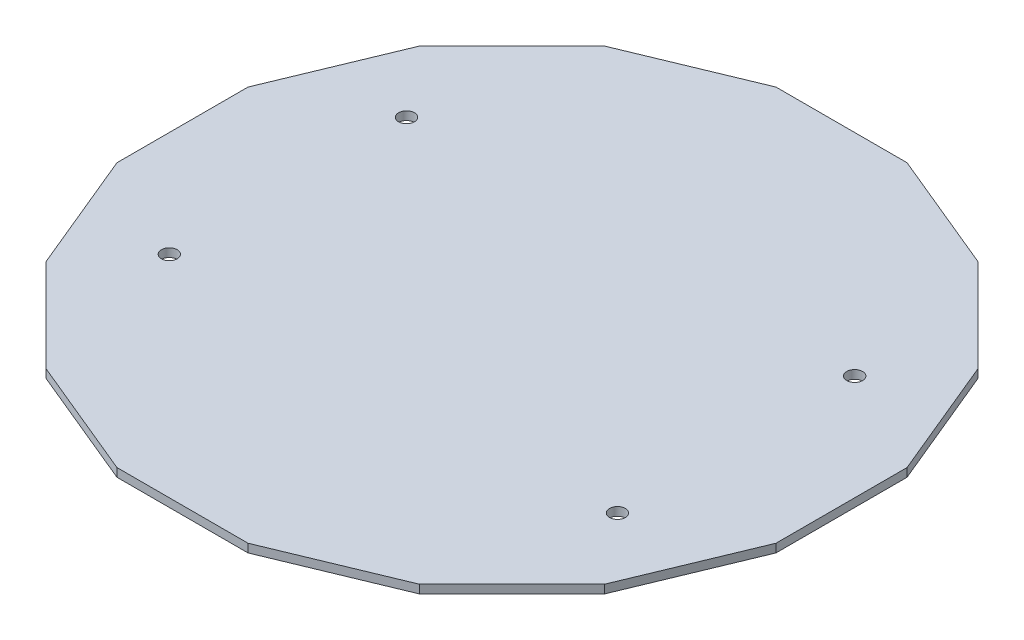
SolidWorks part; units mm, degrees
ref_plane "Front Plane" through (0, 0, 0) normal (0, 0, 1) x (1, 0, 0)
ref_plane "Top Plane" through (0, 0, 0) normal (0, 1, 0) x (1, 0, 0)
ref_plane "Right Plane" through (0, 0, 0) normal (1, 0, 0) x (0, 0, -1)
sketch "Sketch1" plane through (0, 0, 0) normal (0, 1, 0) x (1, 0, 0)
  line L1 (62.5, 12.432) -> (52.9849, 35.4034)
  line L2 (52.9849, 35.4034) -> (35.4034, 52.9849)
  line L3 (35.4034, 52.9849) -> (12.432, 62.5)
  line L4 (12.432, 62.5) -> (-12.432, 62.5)
  line L5 (-12.432, 62.5) -> (-35.4034, 52.9849)
  line L6 (-35.4034, 52.9849) -> (-52.9849, 35.4034)
  line L7 (-52.9849, 35.4034) -> (-62.5, 12.432)
  line L8 (-62.5, 12.432) -> (-62.5, -12.432)
  line L9 (-62.5, -12.432) -> (-52.9849, -35.4034)
  line L10 (-52.9849, -35.4034) -> (-35.4034, -52.9849)
  line L11 (-35.4034, -52.9849) -> (-12.432, -62.5)
  line L12 (-12.432, -62.5) -> (12.432, -62.5)
  line L13 (12.432, -62.5) -> (35.4034, -52.9849)
  line L14 (35.4034, -52.9849) -> (52.9849, -35.4034)
  line L15 (52.9849, -35.4034) -> (62.5, -12.432)
  line L16 (62.5, -12.432) -> (62.5, 12.432)
  circle A0 centre (0, 0) radius 62.5 construction
  dimension "D1" = 125
extrude "Boss-Extrude1" add sketch "Sketch1" along normal blind 1.6
sketch "Sketch2" plane through (0, 0, 0) normal (0, -1, 0) x (1, 0, 0)
  line L0 (-7.5, 62.5) -> (-3.3143, 51)
  line L1 (-12.432, 62.5) -> (12.432, 62.5) construction
  line L2 (-3.3143, 51) -> (3.3143, 51)
  line L3 (3.3143, 51) -> (7.5, 62.5)
  line L4 (7.5, 62.5) -> (9.0963, 62.5)
  line L5 (9.0963, 62.5) -> (4.3647, 49.5)
  line L6 (4.3647, 49.5) -> (-4.3647, 49.5)
  line L7 (-4.3647, 49.5) -> (-9.0963, 62.5)
  line L8 (-9.0963, 62.5) -> (-7.5, 62.5)
  line L131 (15.5139, 61.2235) -> (16.9886, 60.6126)
  line L132 (16.9886, 60.6126) -> (16.4548, 48.3862)
  line L133 (16.4548, 48.3862) -> (22.5789, 45.8495)
  line L134 (22.5789, 45.8495) -> (30.8468, 54.8723)
  line L135 (30.8468, 54.8723) -> (32.3216, 54.2615)
  line L136 (32.3216, 54.2615) -> (22.9752, 44.0618)
  line L137 (22.9752, 44.0618) -> (14.9104, 47.4023)
  line L138 (14.9104, 47.4023) -> (15.5139, 61.2235)
  line L139 (37.7621, 50.6262) -> (38.8909, 49.4975)
  line L140 (38.8909, 49.4975) -> (33.7189, 38.406)
  line L141 (33.7189, 38.406) -> (38.406, 33.7189)
  line L142 (38.406, 33.7189) -> (49.4975, 38.8909)
  line L143 (49.4975, 38.8909) -> (50.6262, 37.7621)
  line L144 (50.6262, 37.7621) -> (38.0881, 31.9155)
  line L145 (38.0881, 31.9155) -> (31.9155, 38.0881)
  line L146 (31.9155, 38.0881) -> (37.7621, 50.6262)
  line L147 (54.2615, 32.3216) -> (54.8723, 30.8468)
  line L148 (54.8723, 30.8468) -> (45.8495, 22.5789)
  line L149 (45.8495, 22.5789) -> (48.3862, 16.4548)
  line L150 (48.3862, 16.4548) -> (60.6126, 16.9886)
  line L151 (60.6126, 16.9886) -> (61.2235, 15.5139)
  line L152 (61.2235, 15.5139) -> (47.4023, 14.9104)
  line L153 (47.4023, 14.9104) -> (44.0618, 22.9752)
  line L154 (44.0618, 22.9752) -> (54.2615, 32.3216)
  line L155 (62.5, 9.0963) -> (62.5, 7.5)
  line L156 (62.5, 7.5) -> (51, 3.3143)
  line L157 (51, 3.3143) -> (51, -3.3143)
  line L158 (51, -3.3143) -> (62.5, -7.5)
  line L167 (62.5, -7.5) -> (62.5, -9.0963)
  line L184 (62.5, -9.0963) -> (49.5, -4.3647)
  line L185 (49.5, -4.3647) -> (49.5, 4.3647)
  line L186 (49.5, 4.3647) -> (62.5, 9.0963)
  line L187 (61.2235, -15.5139) -> (60.6126, -16.9886)
  line L188 (60.6126, -16.9886) -> (48.3862, -16.4548)
  line L189 (48.3862, -16.4548) -> (45.8495, -22.5789)
  line L190 (45.8495, -22.5789) -> (54.8723, -30.8468)
  line L191 (54.8723, -30.8468) -> (54.2615, -32.3216)
  line L192 (54.2615, -32.3216) -> (44.0618, -22.9752)
  line L193 (44.0618, -22.9752) -> (47.4023, -14.9104)
  line L194 (47.4023, -14.9104) -> (61.2235, -15.5139)
  line L195 (50.6262, -37.7621) -> (49.4975, -38.8909)
  line L196 (49.4975, -38.8909) -> (38.406, -33.7189)
  line L197 (38.406, -33.7189) -> (33.7189, -38.406)
  line L198 (33.7189, -38.406) -> (38.8909, -49.4975)
  line L199 (38.8909, -49.4975) -> (37.7621, -50.6262)
  line L200 (37.7621, -50.6262) -> (31.9155, -38.0881)
  line L201 (31.9155, -38.0881) -> (38.0881, -31.9155)
  line L202 (38.0881, -31.9155) -> (50.6262, -37.7621)
  line L203 (32.3216, -54.2615) -> (30.8468, -54.8723)
  line L204 (30.8468, -54.8723) -> (22.5789, -45.8495)
  line L205 (22.5789, -45.8495) -> (16.4548, -48.3862)
  line L206 (16.4548, -48.3862) -> (16.9886, -60.6126)
  line L207 (16.9886, -60.6126) -> (15.5139, -61.2235)
  line L208 (15.5139, -61.2235) -> (14.9104, -47.4023)
  line L209 (14.9104, -47.4023) -> (22.9752, -44.0618)
  line L210 (22.9752, -44.0618) -> (32.3216, -54.2615)
  line L211 (9.0963, -62.5) -> (7.5, -62.5)
  line L212 (7.5, -62.5) -> (3.3143, -51)
  line L213 (3.3143, -51) -> (-3.3143, -51)
  line L214 (-3.3143, -51) -> (-7.5, -62.5)
  line L215 (-7.5, -62.5) -> (-9.0963, -62.5)
  line L216 (-9.0963, -62.5) -> (-4.3647, -49.5)
  line L217 (-4.3647, -49.5) -> (4.3647, -49.5)
  line L218 (4.3647, -49.5) -> (9.0963, -62.5)
  line L219 (-15.5139, -61.2235) -> (-16.9886, -60.6126)
  line L220 (-16.9886, -60.6126) -> (-16.4548, -48.3862)
  line L221 (-16.4548, -48.3862) -> (-22.5789, -45.8495)
  line L222 (-22.5789, -45.8495) -> (-30.8468, -54.8723)
  line L223 (-30.8468, -54.8723) -> (-32.3216, -54.2615)
  line L224 (-32.3216, -54.2615) -> (-22.9752, -44.0618)
  line L225 (-22.9752, -44.0618) -> (-14.9104, -47.4023)
  line L226 (-14.9104, -47.4023) -> (-15.5139, -61.2235)
  line L227 (-37.7621, -50.6262) -> (-38.8909, -49.4975)
  line L228 (-38.8909, -49.4975) -> (-33.7189, -38.406)
  line L229 (-33.7189, -38.406) -> (-38.406, -33.7189)
  line L230 (-38.406, -33.7189) -> (-49.4975, -38.8909)
  line L231 (-49.4975, -38.8909) -> (-50.6262, -37.7621)
  line L232 (-50.6262, -37.7621) -> (-38.0881, -31.9155)
  line L233 (-38.0881, -31.9155) -> (-31.9155, -38.0881)
  line L234 (-31.9155, -38.0881) -> (-37.7621, -50.6262)
  line L235 (-54.2615, -32.3216) -> (-54.8723, -30.8468)
  line L236 (-54.8723, -30.8468) -> (-45.8495, -22.5789)
  line L237 (-45.8495, -22.5789) -> (-48.3862, -16.4548)
  line L238 (-48.3862, -16.4548) -> (-60.6126, -16.9886)
  line L239 (-60.6126, -16.9886) -> (-61.2235, -15.5139)
  line L240 (-61.2235, -15.5139) -> (-47.4023, -14.9104)
  line L241 (-47.4023, -14.9104) -> (-44.0618, -22.9752)
  line L242 (-44.0618, -22.9752) -> (-54.2615, -32.3216)
  line L243 (-62.5, -9.0963) -> (-62.5, -7.5)
  line L244 (-62.5, -7.5) -> (-51, -3.3143)
  line L245 (-51, -3.3143) -> (-51, 3.3143)
  line L246 (-51, 3.3143) -> (-62.5, 7.5)
  line L247 (-62.5, 7.5) -> (-62.5, 9.0963)
  line L248 (-62.5, 9.0963) -> (-49.5, 4.3647)
  line L249 (-49.5, 4.3647) -> (-49.5, -4.3647)
  line L250 (-49.5, -4.3647) -> (-62.5, -9.0963)
  line L251 (-61.2235, 15.5139) -> (-60.6126, 16.9886)
  line L252 (-60.6126, 16.9886) -> (-48.3862, 16.4548)
  line L253 (-48.3862, 16.4548) -> (-45.8495, 22.5789)
  line L254 (-45.8495, 22.5789) -> (-54.8723, 30.8468)
  line L255 (-54.8723, 30.8468) -> (-54.2615, 32.3216)
  line L256 (-54.2615, 32.3216) -> (-44.0618, 22.9752)
  line L257 (-44.0618, 22.9752) -> (-47.4023, 14.9104)
  line L258 (-47.4023, 14.9104) -> (-61.2235, 15.5139)
  line L259 (-50.6262, 37.7621) -> (-49.4975, 38.8909)
  line L260 (-49.4975, 38.8909) -> (-38.406, 33.7189)
  line L261 (-38.406, 33.7189) -> (-33.7189, 38.406)
  line L262 (-33.7189, 38.406) -> (-38.8909, 49.4975)
  line L263 (-38.8909, 49.4975) -> (-37.7621, 50.6262)
  line L264 (-37.7621, 50.6262) -> (-31.9155, 38.0881)
  line L265 (-31.9155, 38.0881) -> (-38.0881, 31.9155)
  line L266 (-38.0881, 31.9155) -> (-50.6262, 37.7621)
  line L267 (-32.3216, 54.2615) -> (-30.8468, 54.8723)
  line L268 (-30.8468, 54.8723) -> (-22.5789, 45.8495)
  line L269 (-22.5789, 45.8495) -> (-16.4548, 48.3862)
  line L270 (-16.4548, 48.3862) -> (-16.9886, 60.6126)
  line L271 (-16.9886, 60.6126) -> (-15.5139, 61.2235)
  line L272 (-15.5139, 61.2235) -> (-14.9104, 47.4023)
  line L273 (-14.9104, 47.4023) -> (-22.9752, 44.0618)
  line L274 (-22.9752, 44.0618) -> (-32.3216, 54.2615)
  point P4 (0, 51)
  point P11 (0, 49.5)
  point P13 (0, 0)
  point P136 (0, 0)
  point P138 (0, 0)
  dimension "D6" = 16
  dimension "D1" = 1.5
  dimension "D2" = 1.5
  dimension "D3" = 15
  dimension "D4" = 40
  dimension "D5" = 11.5
extrude "Boss-Extrude5" [suppressed] add sketch "Sketch2" along normal blind 6
sketch "Sketch6" plane through (0, 1.6, 0) normal (0, 1, 0) x (1, 0, 0)
  line L1 (-42.5, -22.5) -> (42.5, -22.5) construction
  line L2 (-42.5, -22.5) -> (-42.5, 22.5) construction
  line L3 (-42.5, 22.5) -> (42.5, 22.5) construction
  line L4 (42.5, -22.5) -> (42.5, 22.5) construction
  line L5 (-42.5, -22.5) -> (42.5, 22.5) construction
  line L6 (-42.5, 22.5) -> (42.5, -22.5) construction
  circle A0 centre (-42.5, 22.5) radius 1.5
  circle A1 centre (-42.5, -22.5) radius 1.5
  circle A2 centre (42.5, -22.5) radius 1.5
  circle A3 centre (42.5, 22.5) radius 1.5
  point P0 (0, 0)
  dimension "D3" = 3
  dimension "D1" = 85
  dimension "D2" = 45
extrude "Cut-Extrude2" cut sketch "Sketch6" against normal up to surface (1.6 mm away) up to face at (0, 0, 0)
sketch "Sketch17" [suppressed] plane through (0, -6, 0) normal (0, -1, 0) x (1, 0, 0)
  line L1 (-9.8462, 49.5) -> (-28.0395, 41.9641)
  line L2 (-28.0395, 41.9641) -> (-41.9641, 28.0395)
  line L3 (-41.9641, 28.0395) -> (-49.5, 9.8462)
  line L4 (-49.5, 9.8462) -> (-49.5, -9.8462)
  line L5 (-49.5, -9.8462) -> (-41.9641, -28.0395)
  line L6 (-41.9641, -28.0395) -> (-28.0395, -41.9641)
  line L7 (-28.0395, -41.9641) -> (-9.8462, -49.5)
  line L8 (-9.8462, -49.5) -> (9.8462, -49.5)
  line L9 (9.8462, -49.5) -> (28.0395, -41.9641)
  line L10 (28.0395, -41.9641) -> (41.9641, -28.0395)
  line L11 (41.9641, -28.0395) -> (49.5, -9.8462)
  line L12 (49.5, -9.8462) -> (49.5, 9.8462)
  line L13 (49.5, 9.8462) -> (41.9641, 28.0395)
  line L14 (41.9641, 28.0395) -> (28.0395, 41.9641)
  line L15 (28.0395, 41.9641) -> (9.8462, 49.5)
  line L16 (9.8462, 49.5) -> (-9.8462, 49.5)
  line L18 (-49.5, -4.3647) -> (-49.5, 4.3647) construction
  line L20 (-10.1445, 51) -> (-28.8892, 43.2357)
  line L21 (-28.8892, 43.2357) -> (-43.2357, 28.8892)
  line L22 (-43.2357, 28.8892) -> (-51, 10.1445)
  line L23 (-51, 10.1445) -> (-51, -10.1445)
  line L24 (-51, -10.1445) -> (-43.2357, -28.8892)
  line L25 (-43.2357, -28.8892) -> (-28.8892, -43.2357)
  line L26 (-28.8892, -43.2357) -> (-10.1445, -51)
  line L27 (-10.1445, -51) -> (10.1445, -51)
  line L28 (10.1445, -51) -> (28.8892, -43.2357)
  line L29 (28.8892, -43.2357) -> (43.2357, -28.8892)
  line L30 (43.2357, -28.8892) -> (51, -10.1445)
  line L31 (51, -10.1445) -> (51, 10.1445)
  line L32 (51, 10.1445) -> (43.2357, 28.8892)
  line L33 (43.2357, 28.8892) -> (28.8892, 43.2357)
  line L34 (28.8892, 43.2357) -> (10.1445, 51)
  line L35 (10.1445, 51) -> (-10.1445, 51)
  line L36 (-51, 3.3143) -> (-51, -3.3143) construction
  circle A0 centre (0, 0) radius 49.5 construction
  circle A1 centre (0, 0) radius 51 construction
extrude "Boss-Extrude9" [suppressed] add sketch "Sketch17" against normal up to surface (6 mm away)
sketch "Sketch16" [suppressed] plane through (0, -6, 0) normal (0, -1, 0) x (1, 0, 0)
  line L0 (-49.5, 9.8462) -> (-41.9641, 28.0395) construction
  line L1 (-43.8477, 19.2462) -> (-40.356, 19.7059)
  line L2 (-40.356, 19.7059) -> (-39.0083, 22.9597)
  line L3 (-39.0083, 22.9597) -> (-41.1523, 25.7538)
  line L4 (-41.1523, 25.7538) -> (-44.644, 25.2941)
  line L5 (-44.644, 25.2941) -> (-45.9917, 22.0403)
  line L6 (-45.9917, 22.0403) -> (-43.8477, 19.2462)
  line L7 (0, -0.88) -> (0, 0.88) construction
  line L8 (45.9917, 22.0403) -> (43.8477, 19.2462)
  line L9 (44.644, 25.2941) -> (45.9917, 22.0403)
  line L10 (41.1523, 25.7538) -> (44.644, 25.2941)
  line L11 (39.0083, 22.9597) -> (41.1523, 25.7538)
  line L12 (40.356, 19.7059) -> (39.0083, 22.9597)
  line L13 (43.8477, 19.2462) -> (40.356, 19.7059)
  line L14 (0.88, 0) -> (-0.88, 0) construction
  line L15 (44.644, -25.2941) -> (45.9917, -22.0403)
  line L16 (41.1523, -25.7538) -> (44.644, -25.2941)
  line L17 (39.0083, -22.9597) -> (41.1523, -25.7538)
  line L18 (40.356, -19.7059) -> (39.0083, -22.9597)
  line L19 (43.8477, -19.2462) -> (40.356, -19.7059)
  line L20 (45.9917, -22.0403) -> (43.8477, -19.2462)
  line L21 (-45.9917, -22.0403) -> (-43.8477, -19.2462)
  line L22 (-44.644, -25.2941) -> (-45.9917, -22.0403)
  line L23 (-41.1523, -25.7538) -> (-44.644, -25.2941)
  line L24 (-39.0083, -22.9597) -> (-41.1523, -25.7538)
  line L25 (-40.356, -19.7059) -> (-39.0083, -22.9597)
  line L26 (-43.8477, -19.2462) -> (-40.356, -19.7059)
  circle A0 centre (-42.5, 22.5) radius 3.05 construction
  dimension "D1" = 6.1
extrude "Cut-Extrude5" [suppressed] cut sketch "Sketch16" against normal up to surface (6 mm away)
sketch "Sketch21" [suppressed] plane through (0, 0, 0) normal (0, -1, 0) x (1, 0, 0)
  line L0 (-44.644, 25.2941) -> (-45.9917, 22.0403) construction
  line L1 (-47.1365, 21.8896) -> (-45.4317, 19.6678)
  line L5 (-42.5704, 26.5757) -> (-45.3469, 26.2101)
  line L6 (-45.3469, 26.2101) -> (-47.1365, 21.8896)
  line L7 (-45.9917, 22.0403) -> (-44.9898, 20.7347)
  line L11 (-43.0123, 25.5089) -> (-44.644, 25.2941)
  line L12 (-44.644, 25.2941) -> (-45.9917, 22.0403)
  line L13 (-43.0123, 25.5089) -> (-42.5704, 26.5757)
  line L15 (-43.0123, 25.5089) -> (-41.9641, 28.0395) construction
  line L16 (-44.9898, 20.7347) -> (-45.4317, 19.6678)
  line L17 (-49.5, 9.8462) -> (-44.9898, 20.7347) construction
  line L18 (0, -4.18) -> (0, 4.18) construction
  line L19 (-42.1019, 19.4761) -> (-40.356, 19.7059) [skipped]
  line L20 (-41.9714, 18.4846) -> (-39.6531, 18.7899) [skipped]
  line L21 (-38.7583, 20.9501) -> (-37.8635, 23.1104) [skipped]
  line L22 (-39.6822, 21.3328) -> (-39.0083, 22.9597) [skipped]
  line L23 (-39.0083, 22.9597) -> (-41.1523, 25.7538) [skipped]
  line L24 (-37.8635, 23.1104) -> (-40.7104, 26.8206) [skipped]
  line L25 (43.0123, 25.5089) -> (42.5704, 26.5757)
  line L26 (42.5704, 26.5757) -> (45.3469, 26.2101)
  line L27 (45.3469, 26.2101) -> (47.1365, 21.8896)
  line L28 (47.1365, 21.8896) -> (45.4317, 19.6678)
  line L29 (44.9898, 20.7347) -> (45.4317, 19.6678)
  line L30 (45.9917, 22.0403) -> (44.9898, 20.7347)
  line L31 (44.644, 25.2941) -> (45.9917, 22.0403)
  line L32 (43.0123, 25.5089) -> (44.644, 25.2941)
  line L33 (4.18, 0) -> (-4.18, 0) construction
  line L34 (43.0123, -25.5089) -> (44.644, -25.2941)
  line L35 (44.644, -25.2941) -> (45.9917, -22.0403)
  line L36 (45.9917, -22.0403) -> (44.9898, -20.7347)
  line L37 (44.9898, -20.7347) -> (45.4317, -19.6678)
  line L38 (47.1365, -21.8896) -> (45.4317, -19.6678)
  line L39 (45.3469, -26.2101) -> (47.1365, -21.8896)
  line L40 (42.5704, -26.5757) -> (45.3469, -26.2101)
  line L41 (43.0123, -25.5089) -> (42.5704, -26.5757)
  line L42 (-44.9898, -20.7347) -> (-45.4317, -19.6678)
  line L43 (-43.0123, -25.5089) -> (-42.5704, -26.5757)
  line L44 (-44.644, -25.2941) -> (-45.9917, -22.0403)
  line L45 (-43.0123, -25.5089) -> (-44.644, -25.2941)
  line L46 (-45.9917, -22.0403) -> (-44.9898, -20.7347)
  line L47 (-45.3469, -26.2101) -> (-47.1365, -21.8896)
  line L48 (-42.5704, -26.5757) -> (-45.3469, -26.2101)
  line L49 (-47.1365, -21.8896) -> (-45.4317, -19.6678)
  arc A0 (-42.5814, 26.5492) -> (-45.4208, 19.6943) centre (-42.5, 22.5) ccw construction
  arc A1 (-42.5814, -26.5492) -> (-45.4208, -19.6943) centre (-42.5, -22.5) cw construction
  dimension "D1" = 1
extrude "Boss-Extrude11" [suppressed] add sketch "Sketch21" along normal up to surface (6 mm away)
sketch "Sketch22" [suppressed] plane through (0, 0, 0) normal (0, -1, 0) x (1, 0, 0)
  line L0 (45.9917, 22.0403) -> (44.644, 25.2941) construction
  line L1 (44.644, 25.2941) -> (41.1523, 25.7538)
  line L2 (41.1523, 25.7538) -> (39.0083, 22.9597)
  line L3 (39.0083, 22.9597) -> (40.356, 19.7059)
  line L4 (40.356, 19.7059) -> (43.8477, 19.2462)
  line L5 (43.8477, 19.2462) -> (45.9917, 22.0403)
  line L6 (45.9917, 22.0403) -> (44.644, 25.2941)
  line L7 (0, -4.18) -> (0, 4.18) construction
  line L8 (-45.9917, 22.0403) -> (-44.644, 25.2941)
  line L9 (-43.8477, 19.2462) -> (-45.9917, 22.0403)
  line L10 (-40.356, 19.7059) -> (-43.8477, 19.2462)
  line L11 (-39.0083, 22.9597) -> (-40.356, 19.7059)
  line L12 (-41.1523, 25.7538) -> (-39.0083, 22.9597)
  line L13 (-44.644, 25.2941) -> (-41.1523, 25.7538)
  line L14 (4.18, 0) -> (-4.18, 0) construction
  line L15 (-44.644, -25.2941) -> (-41.1523, -25.7538)
  line L16 (-41.1523, -25.7538) -> (-39.0083, -22.9597)
  line L17 (-39.0083, -22.9597) -> (-40.356, -19.7059)
  line L18 (-40.356, -19.7059) -> (-43.8477, -19.2462)
  line L19 (-43.8477, -19.2462) -> (-45.9917, -22.0403)
  line L20 (-45.9917, -22.0403) -> (-44.644, -25.2941)
  line L21 (45.9917, -22.0403) -> (44.644, -25.2941)
  line L22 (43.8477, -19.2462) -> (45.9917, -22.0403)
  line L23 (40.356, -19.7059) -> (43.8477, -19.2462)
  line L24 (39.0083, -22.9597) -> (40.356, -19.7059)
  line L25 (41.1523, -25.7538) -> (39.0083, -22.9597)
  line L26 (44.644, -25.2941) -> (41.1523, -25.7538)
  circle A0 centre (42.5, 22.5) radius 3.05 construction
  circle A1 centre (42.5, 22.5) radius 1.5
  circle A2 centre (42.5, 22.5) radius 1.5 construction
  circle A3 centre (42.5, -22.5) radius 3.05 construction
  circle A4 centre (42.5, -22.5) radius 1.5
  circle A5 centre (-42.5, 22.5) radius 1.5
  circle A6 centre (-42.5, -22.5) radius 1.5
extrude "Boss-Extrude12" [suppressed] add sketch "Sketch22" along normal blind 2
sketch "Sketch23" [suppressed] plane through (0, -2, 0) normal (0, -1, 0) x (1, 0, 0)
  line L0 (-41.1523, 25.7538) -> (-42.2943, 27.2422)
  line L1 (-43.0123, 25.5089) -> (-41.9641, 28.0395) construction
  line L2 (-43.8477, 19.2462) -> (-45.7078, 19.0014)
  line L3 (-49.5, 9.8462) -> (-44.9898, 20.7347) construction
  line L4 (-43.8477, 19.2462) -> (-40.356, 19.7059) construction
  line L5 (-39.0083, 22.9597) -> (-41.1523, 25.7538) construction
  line L6 (-42.2943, 27.2422) -> (-43.0123, 25.5089)
  line L7 (-43.0123, 25.5089) -> (-41.1523, 25.7538)
  line L8 (-44.9898, 20.7347) -> (-43.8477, 19.2462)
  line L9 (-45.7078, 19.0014) -> (-44.9898, 20.7347)
  line L10 (4.18, 0) -> (-4.18, 0) construction
  line L11 (-43.8477, -19.2462) -> (-45.7078, -19.0014)
  line L12 (-44.9898, -20.7347) -> (-43.8477, -19.2462)
  line L13 (-45.7078, -19.0014) -> (-44.9898, -20.7347)
  line L14 (-42.2943, -27.2422) -> (-43.0123, -25.5089)
  line L15 (-41.1523, -25.7538) -> (-42.2943, -27.2422)
  line L16 (-43.0123, -25.5089) -> (-41.1523, -25.7538)
  line L17 (0, -4.18) -> (0, 4.18) construction
  line L18 (43.0123, -25.5089) -> (41.1523, -25.7538)
  line L19 (41.1523, -25.7538) -> (42.2943, -27.2422)
  line L20 (42.2943, -27.2422) -> (43.0123, -25.5089)
  line L21 (45.7078, -19.0014) -> (44.9898, -20.7347)
  line L22 (44.9898, -20.7347) -> (43.8477, -19.2462)
  line L23 (43.8477, -19.2462) -> (45.7078, -19.0014)
  line L24 (45.7078, 19.0014) -> (44.9898, 20.7347)
  line L25 (44.9898, 20.7347) -> (43.8477, 19.2462)
  line L26 (43.0123, 25.5089) -> (41.1523, 25.7538)
  line L27 (42.2943, 27.2422) -> (43.0123, 25.5089)
  line L28 (43.8477, 19.2462) -> (45.7078, 19.0014)
  line L29 (41.1523, 25.7538) -> (42.2943, 27.2422)
extrude "Boss-Extrude13" [suppressed] add sketch "Sketch23" against normal up to surface (2 mm away)
sketch "Sketch24" [suppressed] plane through (0, 0, 0) normal (0, -1, 0) x (1, 0, 0)
  line L0 (-12.432, 62.5) -> (-15.5139, 61.2235)
  line L1 (-15.5139, 61.2235) -> (-14.98, 48.9971)
  line L2 (-14.98, 48.9971) -> (-10.1445, 51)
  line L3 (-10.1445, 51) -> (-4.9106, 51)
  line L4 (-4.9106, 51) -> (-9.0963, 62.5)
  line L5 (-9.0963, 62.5) -> (-12.432, 62.5)
  line L6 (15.5139, 61.2235) -> (12.432, 62.5)
  line L7 (12.432, 62.5) -> (9.0963, 62.5)
  line L8 (9.0963, 62.5) -> (4.9106, 51)
  line L9 (4.9106, 51) -> (10.1445, 51)
  line L10 (10.1445, 51) -> (14.98, 48.9971)
  line L11 (14.98, 48.9971) -> (15.5139, 61.2235)
  line L12 (37.7621, 50.6262) -> (35.4034, 52.9849)
  line L13 (35.4034, 52.9849) -> (32.3216, 54.2615)
  line L14 (32.3216, 54.2615) -> (24.0537, 45.2386)
  line L15 (24.0537, 45.2386) -> (28.8892, 43.2357)
  line L16 (28.8892, 43.2357) -> (32.5901, 39.5348)
  line L17 (32.5901, 39.5348) -> (37.7621, 50.6262)
  line L18 (54.2615, 32.3216) -> (52.9849, 35.4034)
  line L19 (52.9849, 35.4034) -> (50.6262, 37.7621)
  line L20 (50.6262, 37.7621) -> (39.5348, 32.5901)
  line L21 (39.5348, 32.5901) -> (43.2357, 28.8892)
  line L22 (43.2357, 28.8892) -> (45.2386, 24.0537)
  line L23 (45.2386, 24.0537) -> (54.2615, 32.3216)
  line L24 (62.5, 9.0963) -> (62.5, 12.432)
  line L25 (62.5, 12.432) -> (61.2235, 15.5139)
  line L26 (61.2235, 15.5139) -> (48.9971, 14.98)
  line L27 (48.9971, 14.98) -> (51, 10.1445)
  line L28 (51, 10.1445) -> (51, 4.9106)
  line L29 (51, 4.9106) -> (62.5, 9.0963)
  line L30 (61.2235, -15.5139) -> (62.5, -12.432)
  line L31 (62.5, -12.432) -> (62.5, -9.0963)
  line L32 (62.5, -9.0963) -> (51, -4.9106)
  line L33 (51, -4.9106) -> (51, -10.1445)
  line L34 (51, -10.1445) -> (48.9971, -14.98)
  line L35 (48.9971, -14.98) -> (61.2235, -15.5139)
  line L36 (50.6262, -37.7621) -> (52.9849, -35.4034)
  line L37 (52.9849, -35.4034) -> (54.2615, -32.3216)
  line L38 (54.2615, -32.3216) -> (45.2386, -24.0537)
  line L39 (45.2386, -24.0537) -> (43.2357, -28.8892)
  line L40 (43.2357, -28.8892) -> (39.5348, -32.5901)
  line L41 (39.5348, -32.5901) -> (50.6262, -37.7621)
  line L42 (32.3216, -54.2615) -> (35.4034, -52.9849)
  line L43 (35.4034, -52.9849) -> (37.7621, -50.6262)
  line L44 (37.7621, -50.6262) -> (32.5901, -39.5348)
  line L45 (32.5901, -39.5348) -> (28.8892, -43.2357)
  line L46 (28.8892, -43.2357) -> (24.0537, -45.2386)
  line L47 (24.0537, -45.2386) -> (32.3216, -54.2615)
  line L48 (9.0963, -62.5) -> (12.432, -62.5)
  line L49 (12.432, -62.5) -> (15.5139, -61.2235)
  line L50 (15.5139, -61.2235) -> (14.98, -48.9971)
  line L51 (14.98, -48.9971) -> (10.1445, -51)
  line L52 (10.1445, -51) -> (4.9106, -51)
  line L53 (4.9106, -51) -> (9.0963, -62.5)
  line L54 (-15.5139, -61.2235) -> (-12.432, -62.5)
  line L55 (-12.432, -62.5) -> (-9.0963, -62.5)
  line L56 (-9.0963, -62.5) -> (-4.9106, -51)
  line L57 (-4.9106, -51) -> (-10.1445, -51)
  line L58 (-10.1445, -51) -> (-14.98, -48.9971)
  line L59 (-14.98, -48.9971) -> (-15.5139, -61.2235)
  line L60 (-37.7621, -50.6262) -> (-35.4034, -52.9849)
  line L61 (-35.4034, -52.9849) -> (-32.3216, -54.2615)
  line L62 (-32.3216, -54.2615) -> (-24.0537, -45.2386)
  line L63 (-24.0537, -45.2386) -> (-28.8892, -43.2357)
  line L64 (-28.8892, -43.2357) -> (-32.5901, -39.5348)
  line L65 (-32.5901, -39.5348) -> (-37.7621, -50.6262)
  line L66 (-54.2615, -32.3216) -> (-52.9849, -35.4034)
  line L67 (-52.9849, -35.4034) -> (-50.6262, -37.7621)
  line L68 (-50.6262, -37.7621) -> (-39.5348, -32.5901)
  line L69 (-39.5348, -32.5901) -> (-43.2357, -28.8892)
  line L70 (-43.2357, -28.8892) -> (-45.2386, -24.0537)
  line L71 (-45.2386, -24.0537) -> (-54.2615, -32.3216)
  line L72 (-62.5, -9.0963) -> (-62.5, -12.432)
  line L73 (-62.5, -12.432) -> (-61.2235, -15.5139)
  line L74 (-61.2235, -15.5139) -> (-48.9971, -14.98)
  line L75 (-48.9971, -14.98) -> (-51, -10.1445)
  line L76 (-51, -10.1445) -> (-51, -4.9106)
  line L77 (-51, -4.9106) -> (-62.5, -9.0963)
  line L78 (-61.2235, 15.5139) -> (-62.5, 12.432)
  line L79 (-62.5, 12.432) -> (-62.5, 9.0963)
  line L80 (-62.5, 9.0963) -> (-51, 4.9106)
  line L81 (-51, 4.9106) -> (-51, 10.1445)
  line L82 (-51, 10.1445) -> (-48.9971, 14.98)
  line L83 (-48.9971, 14.98) -> (-61.2235, 15.5139)
  line L84 (-50.6262, 37.7621) -> (-52.9849, 35.4034)
  line L85 (-52.9849, 35.4034) -> (-54.2615, 32.3216)
  line L86 (-54.2615, 32.3216) -> (-45.2386, 24.0537)
  line L87 (-45.2386, 24.0537) -> (-43.2357, 28.8892)
  line L88 (-43.2357, 28.8892) -> (-39.5348, 32.5901)
  line L89 (-39.5348, 32.5901) -> (-50.6262, 37.7621)
  line L90 (-32.3216, 54.2615) -> (-35.4034, 52.9849)
  line L91 (-35.4034, 52.9849) -> (-37.7621, 50.6262)
  line L92 (-37.7621, 50.6262) -> (-32.5901, 39.5348)
  line L93 (-32.5901, 39.5348) -> (-28.8892, 43.2357)
  line L94 (-28.8892, 43.2357) -> (-24.0537, 45.2386)
  line L95 (-24.0537, 45.2386) -> (-32.3216, 54.2615)
  point P4 (0, 0)
  point P104 (0, 0)
  dimension "D1" = 16
extrude "Boss-Extrude15" [suppressed] add sketch "Sketch24" along normal blind 1.5
sketch "Sketch18" plane through (0, 1.6, 0) normal (0, 1, 0) x (1, 0, 0)
  line L0 (-62.5, 12.432) -> (-62.5, -12.432) construction
  line L1 (-35.4034, 52.9849) -> (-52.9849, 35.4034)
  line L2 (-52.9849, 35.4034) -> (-62.5, 12.432)
  line L3 (-62.5, 12.432) -> (-62.5, -12.432)
  line L4 (-62.5, -12.432) -> (-52.9849, -35.4034)
  line L5 (-52.9849, -35.4034) -> (-35.4034, -52.9849)
  line L6 (-35.4034, -52.9849) -> (-12.432, -62.5)
  line L7 (-12.432, -62.5) -> (12.432, -62.5)
  line L8 (12.432, -62.5) -> (35.4034, -52.9849)
  line L9 (35.4034, -52.9849) -> (52.9849, -35.4034)
  line L10 (52.9849, -35.4034) -> (62.5, -12.432)
  line L11 (62.5, -12.432) -> (62.5, 12.432)
  line L12 (62.5, 12.432) -> (52.9849, 35.4034)
  line L13 (52.9849, 35.4034) -> (35.4034, 52.9849)
  line L14 (35.4034, 52.9849) -> (12.432, 62.5)
  line L15 (12.432, 62.5) -> (-12.432, 62.5)
  line L16 (-12.432, 62.5) -> (-35.4034, 52.9849)
  circle A0 centre (0, 0) radius 62.5 construction
extrude "Cut-Extrude6" [suppressed] cut sketch "Sketch18" against normal up to surface (1.6 mm away)
